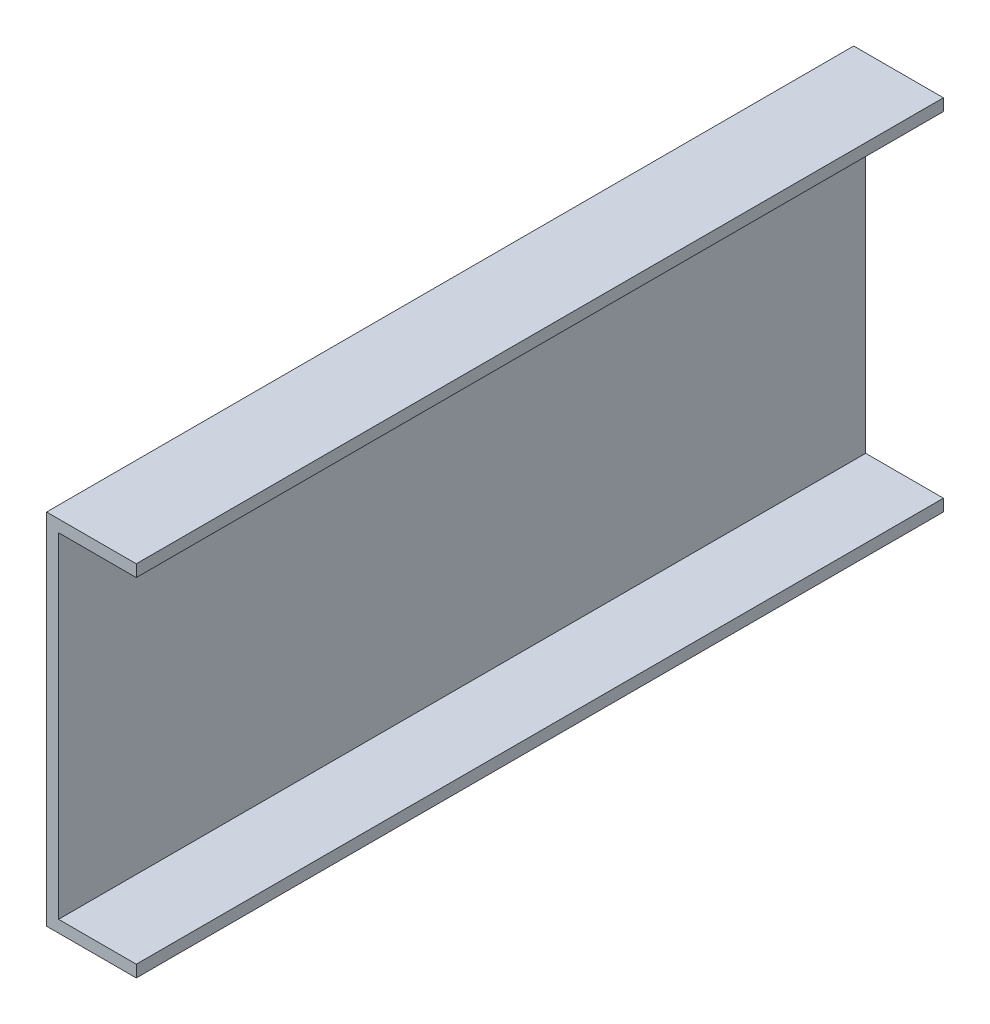
SolidWorks part; units mm, degrees
material "6061 Alloy"
ref_plane "Front Plane" through (0, 0, 0) normal (0, 0, 1) x (1, 0, 0)
ref_plane "Top Plane" through (0, 0, 0) normal (0, 1, 0) x (1, 0, 0)
ref_plane "Right Plane" through (0, 0, 0) normal (1, 0, 0) x (0, 0, -1)
sketch "Sketch1" plane through (0, 0, 0) normal (0, 0, 1) x (1, 0, 0)
  line L0 (-135.1577, 49.7803) -> (-135.1577, -26.4197)
  line L1 (-135.1577, -26.4197) -> (-116.1077, -26.4197)
  line L2 (-135.1577, 49.7803) -> (-116.1077, 49.7803)
  dimension "D1" = 76.2
  dimension "D2" = 19.05
  dimension "D3" = 19.05
extrude "Extrude-Thin1" add sketch "Sketch1" along normal blind 171.45 thin thin type one direction wall 2.54
